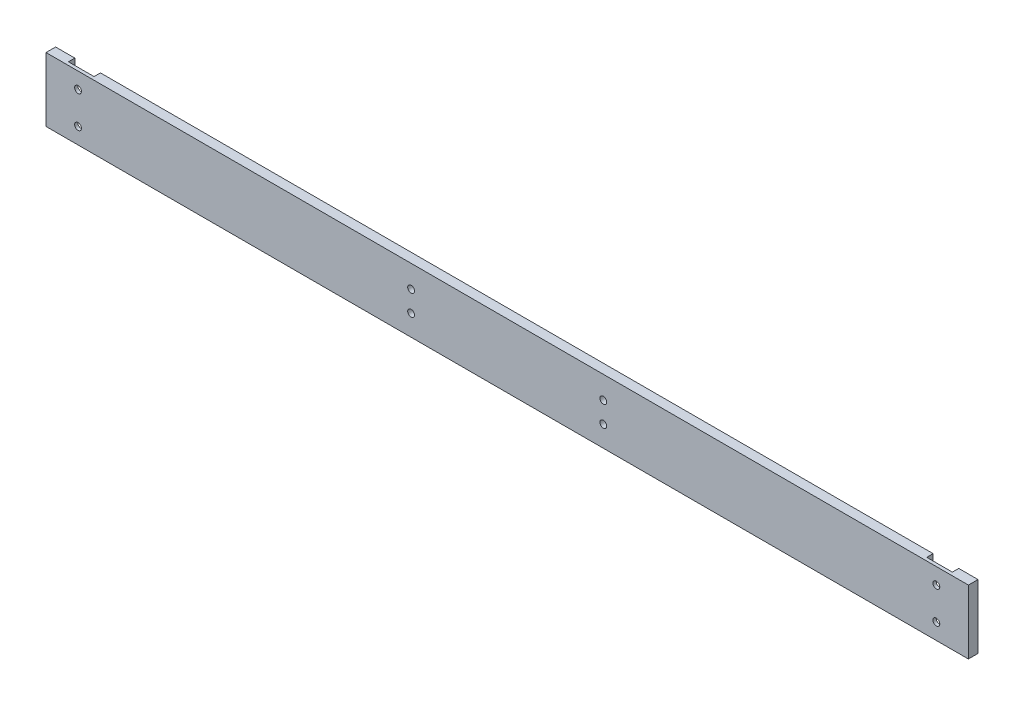
SolidWorks part; units mm, degrees
material "6061 Alloy"
ref_plane "Front Plane" through (0, 0, 0) normal (0, 0, 1) x (1, 0, 0)
ref_plane "Top Plane" through (0, 0, 0) normal (0, 1, 0) x (1, 0, 0)
ref_plane "Right Plane" through (0, 0, 0) normal (1, 0, 0) x (0, 0, -1)
sketch "Sketch1" plane through (0, 0, 0) normal (0, 1, 0) x (1, 0, 0)
  line L1 (-457.2, 0) -> (457.2, 0)
  line L2 (-457.2, 0) -> (-457.2, 9.525)
  line L3 (-457.2, 9.525) -> (457.2, 9.525)
  line L4 (457.2, 0) -> (457.2, 9.525)
  dimension "D1" = 9.525
  dimension "D2" = 914.4
extrude "Boss-Extrude1" add sketch "Sketch1" along normal blind 63.5 contours L3 L4 L1 L2
sketch "Sketch2" plane through (0, 0, -9.525) normal (0, 0, -1) x (-1, 0, 0)
  line L0 (457.2, 0) -> (-457.2, 0) construction
  line L1 (-412.75, 0) -> (-438.15, 0)
  line L2 (-412.75, 0) -> (-412.75, 63.5)
  line L3 (-412.75, 63.5) -> (-438.15, 63.5)
  line L4 (-438.15, 0) -> (-438.15, 63.5)
  line L5 (457.2, 63.5) -> (-457.2, 63.5) construction
  dimension "D1" = 25.4
  dimension "D2" = 412.75
extrude "Cut-Extrude1" cut sketch "Sketch2" against normal blind 6.35
hole_wizard "1/4 Clearance Hole1" positions "Sketch4" profile "Sketch3" hole size "1/4" standard "ANSI Inch" end condition up to next
sketch "Sketch4" plane through (0, 0, 0) normal (0, 0, 1) x (1, 0, 0)
  line L1 (-457.2, 63.5) -> (457.2, 63.5) construction
  point P6 (425.45, 47.625)
  dimension "D1" = 425.45
  dimension "D2" = 15.875
sketch "Sketch3" plane through (425.45, 47.625, 0) normal (1, 0, 0) x (0, -1, 0)
  line L0 (0, 0) -> (0, 3.176)
  line L1 (0, 3.176) -> (3.3782, 3.176)
  line L2 (3.3782, 3.176) -> (3.3782, 0)
  line L5 (3.3782, 0) -> (0, 0)
  line L11 (0, -6.35) -> (0, 107.95) construction
  dimension "Thru Hole Dia." = 6.7564
  dimension "Thru Hole Depth" = 3.176
hole_wizard "1/4 Clearance Hole2" positions "Sketch5" profile "Sketch6" hole size "1/4" standard "ANSI Inch" end condition through all
sketch "Sketch5" plane through (0, 0, 0) normal (0, 0, 1) x (1, 0, 0)
  line L0 (0, 0) -> (0, 63.5) construction
  line L1 (-457.2, 0) -> (457.2, 0) construction
  line L2 (-457.2, 63.5) -> (457.2, 63.5) construction
  point P0 (-95.25, 41.275)
  point P2 (-95.25, 20.6375)
  point P4 (95.25, 41.275)
  point P6 (95.25, 20.6375)
  dimension "D1" = 20.6375
  dimension "D2" = 20.6375
  dimension "D3" = 190.5
sketch "Sketch6" plane through (-95.25, 41.275, 0) normal (1, 0, 0) x (0, -1, 0)
  line L0 (0, 0) -> (0, 9.525)
  line L1 (0, 9.525) -> (3.3782, 9.525)
  line L2 (3.3782, 9.525) -> (3.3782, 0)
  line L5 (3.3782, 0) -> (0, 0)
  line L11 (0, -6.35) -> (0, 107.95) construction
  dimension "Thru Hole Dia." = 6.7564
  dimension "Thru Hole Depth" = 9.525
pattern_linear "LPattern1" count 3 spacing 15.875 along (0, -1, 0) skipping (1, 0) of "1/4 Clearance Hole1"
mirror "Mirror1" about plane through (0, 0, 0) normal (1, 0, 0) of "1/4 Clearance Hole1", "LPattern1", "Cut-Extrude1"
ref_plane "Plane1" through (-425.45, 0, 0) normal (1, 0, 0) x (0, 0, -1)
ref_plane "Plane2" through (425.45, 0, 0) normal (1, 0, 0) x (0, 0, -1)
ref_plane "Plane3" through (0, 31.75, 0) normal (0, -1, 0) x (-1, 0, 0)
